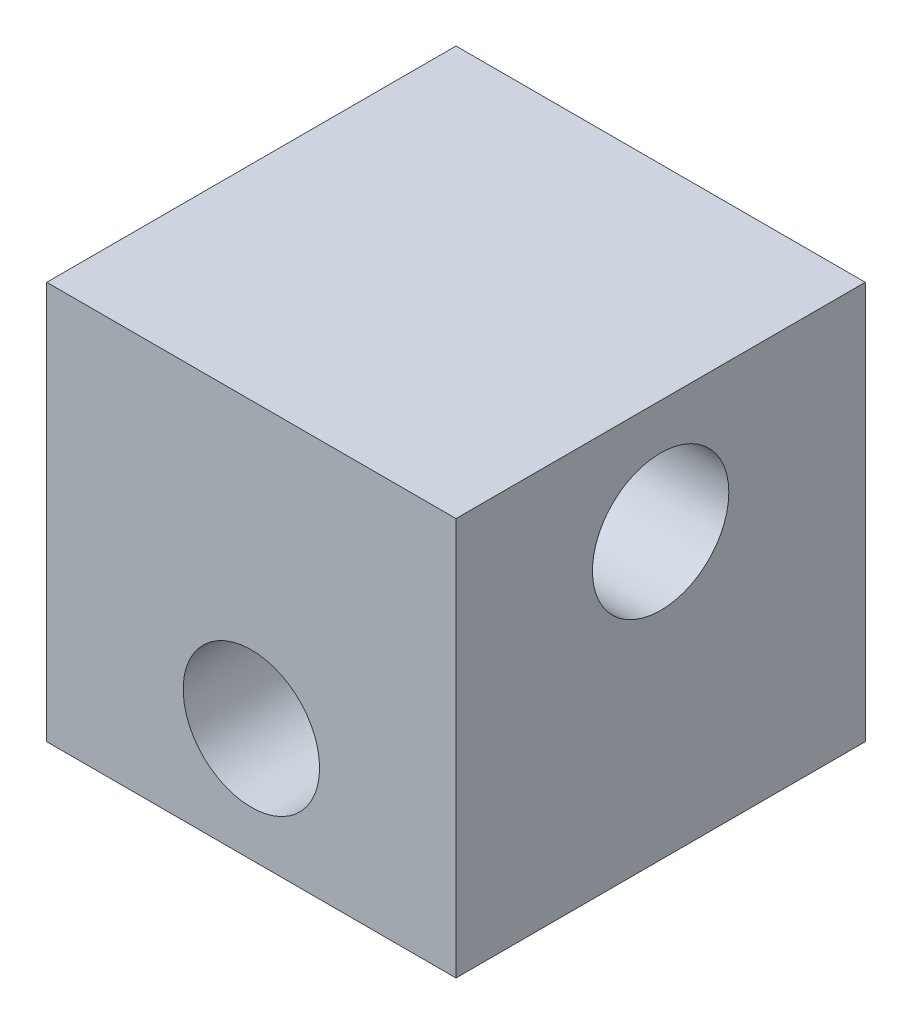
SolidWorks part; units mm, degrees
ref_plane "Front Plane" through (0, 0, 0) normal (0, 0, 1) x (1, 0, 0)
ref_plane "Top Plane" through (0, 0, 0) normal (0, 1, 0) x (1, 0, 0)
ref_plane "Right Plane" through (0, 0, 0) normal (1, 0, 0) x (0, 0, -1)
sketch "Sketch1" plane through (0, 0, 0) normal (0, 1, 0) x (1, 0, 0)
  line L1 (-18, 18) -> (18, 18)
  line L2 (-18, 18) -> (-18, -18)
  line L3 (-18, -18) -> (18, -18)
  line L4 (18, 18) -> (18, -18)
  line L5 (-18, 18) -> (18, -18) construction
  line L6 (-18, -18) -> (18, 18) construction
  point P0 (0, 0)
  dimension "D1" = 36
  dimension "D2" = 36
extrude "Boss-Extrude1" add sketch "Sketch1" along normal blind 35
sketch "Sketch2" plane through (0, 0, 18) normal (0, 0, 1) x (1, 0, 0)
  line L1 (-18, 0) -> (18, 0) construction
  line L2 (0, 35) -> (0, 0) construction
  line L3 (-18, 35) -> (18, 35) construction
  circle A0 centre (0, 10) radius 6
  dimension "D1" = 12
  dimension "D3" = 10
extrude "Cut-Extrude1" cut sketch "Sketch2" against normal through all
sketch "Sketch3" plane through (18, 0, 0) normal (1, 0, 0) x (0, 0, -1)
  line L1 (-18, 35) -> (18, 35) construction
  line L2 (0, 35) -> (0, 0) construction
  line L3 (18, 35) -> (-18, 35) construction
  circle A0 centre (0, 25) radius 6
  dimension "D3" = 12
  dimension "D2" = 10
extrude "Cut-Extrude2" cut sketch "Sketch3" against normal through all
